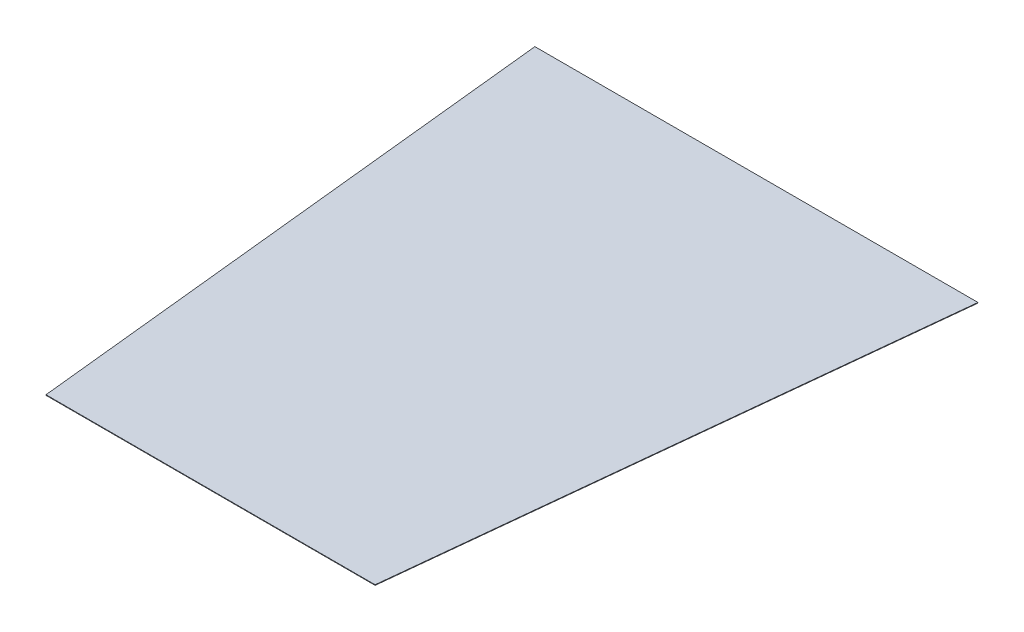
SolidWorks part; units mm, degrees
material "5052-O"
ref_plane "Front Plane" through (0, 0, 0) normal (0, 0, 1) x (1, 0, 0)
ref_plane "Top Plane" through (0, 0, 0) normal (0, 1, 0) x (1, 0, 0)
ref_plane "Right Plane" through (0, 0, 0) normal (1, 0, 0) x (0, 0, -1)
sketch "Sketch1" plane through (0, 0, 0) normal (0, 1, 0) x (1, 0, 0)
  line L0 (-294.245, 0) -> (294.245, 0)
  line L1 (-294.245, 0) -> (-396.16, 976.1039)
  line L2 (-396.16, 976.1039) -> (396.16, 976.1039)
  line L3 (396.16, 976.1039) -> (294.245, 0)
  point P3 (0, 0)
  dimension "D1" = 588.49
  dimension "D2" = 792.32
  dimension "D3" = 981.41
extrude "Center Floor Closeout" add sketch "Sketch1" along normal blind 1
